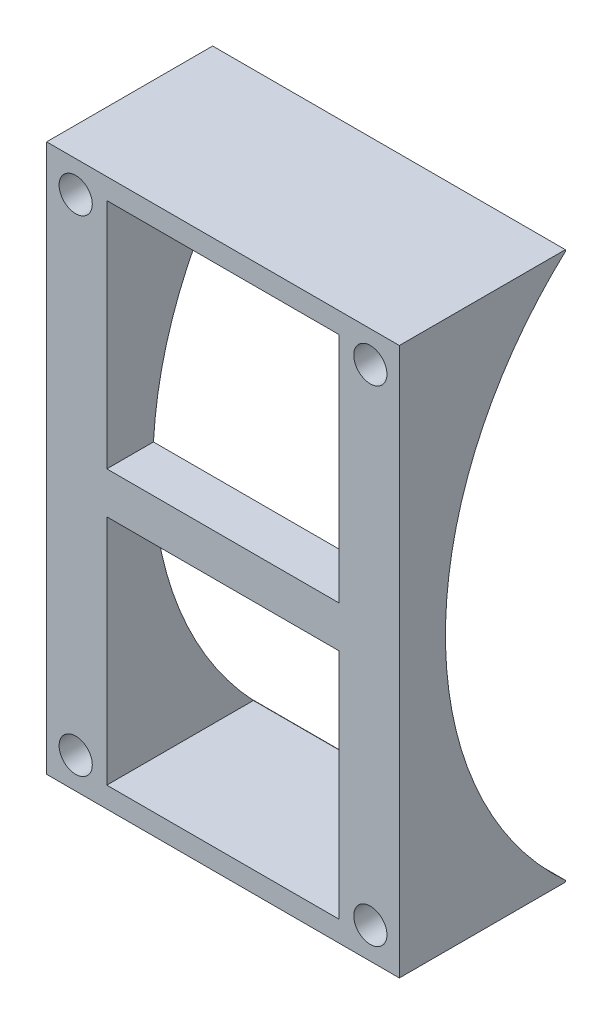
SolidWorks part; units mm, degrees
ref_plane "Front Plane" through (0, 0, 0) normal (0, 0, 1) x (1, 0, 0)
ref_plane "Top Plane" through (0, 0, 0) normal (0, 1, 0) x (1, 0, 0)
ref_plane "Right Plane" through (0, 0, 0) normal (1, 0, 0) x (0, 0, -1)
sketch "Sketch1" plane through (0, 0, 0) normal (0, 0, 1) x (1, 0, 0)
  line L0 (0, -33) -> (0, -16.5) construction
  line L1 (-21.25, 33) -> (21.25, 33)
  line L2 (-21.25, 33) -> (-21.25, -33)
  line L3 (-21.25, -33) -> (21.25, -33)
  line L4 (21.25, 33) -> (21.25, -33)
  line L5 (-21.25, 33) -> (21.25, -33) construction
  line L6 (-21.25, -33) -> (21.25, 33) construction
  line L7 (0, 33) -> (0, 16.5) construction
  line L9 (-14, 30.5) -> (14, 30.5)
  line L10 (-14, 30.5) -> (-14, 2.5)
  line L11 (-14, 2.5) -> (14, 2.5)
  line L12 (14, 30.5) -> (14, 2.5)
  line L13 (-14, 30.5) -> (14, 2.5) construction
  line L14 (-14, 2.5) -> (14, 30.5) construction
  line L15 (-14, -2.5) -> (14, -2.5)
  line L16 (-14, -2.5) -> (-14, -30.5)
  line L17 (-14, -30.5) -> (14, -30.5)
  line L18 (14, -2.5) -> (14, -30.5)
  line L19 (-14, -2.5) -> (14, -30.5) construction
  line L20 (-14, -30.5) -> (14, -2.5) construction
  point P0 (0, 0)
  dimension "D1" = 42.5
  dimension "D2" = 66
  dimension "D3" = 28
  dimension "D4" = 28
  dimension "D5" = 28
  dimension "D6" = 28
  dimension "D7" = 5
extrude "Boss-Extrude1" add sketch "Sketch1" along normal blind 20
sketch "Sketch3" plane through (0, 0, 0) normal (1, 0, 0) x (0, 0, -1)
  line L0 (0, 0) -> (30, 0) construction
  circle A0 centre (30, 0) radius 44.45
  dimension "D1" = 88.9
  dimension "D2" = 30
extrude "Cut-Extrude1" cut sketch "Sketch3" against normal blind 27 and the other way blind 26
sketch "Sketch4" plane through (0, 0, 20) normal (0, 0, 1) x (1, 0, 0)
  circle A0 centre (-17.75, 29.25) radius 2
  circle A1 centre (17.75, 29.25) radius 2
  circle A2 centre (-17.75, -29.25) radius 2
  circle A3 centre (17.75, -29.25) radius 2
  dimension "D1" = 4
  dimension "D4" = 4
  dimension "D7" = 4
  dimension "D10" = 4
  dimension "D2" = 3.75
  dimension "D3" = 3.75
  dimension "D5" = 3.75
  dimension "D6" = 3.75
  dimension "D8" = 3.75
  dimension "D9" = 3.75
  dimension "D11" = 3.75
  dimension "D12" = 3.75
extrude "Cut-Extrude2" cut sketch "Sketch4" against normal blind 27
